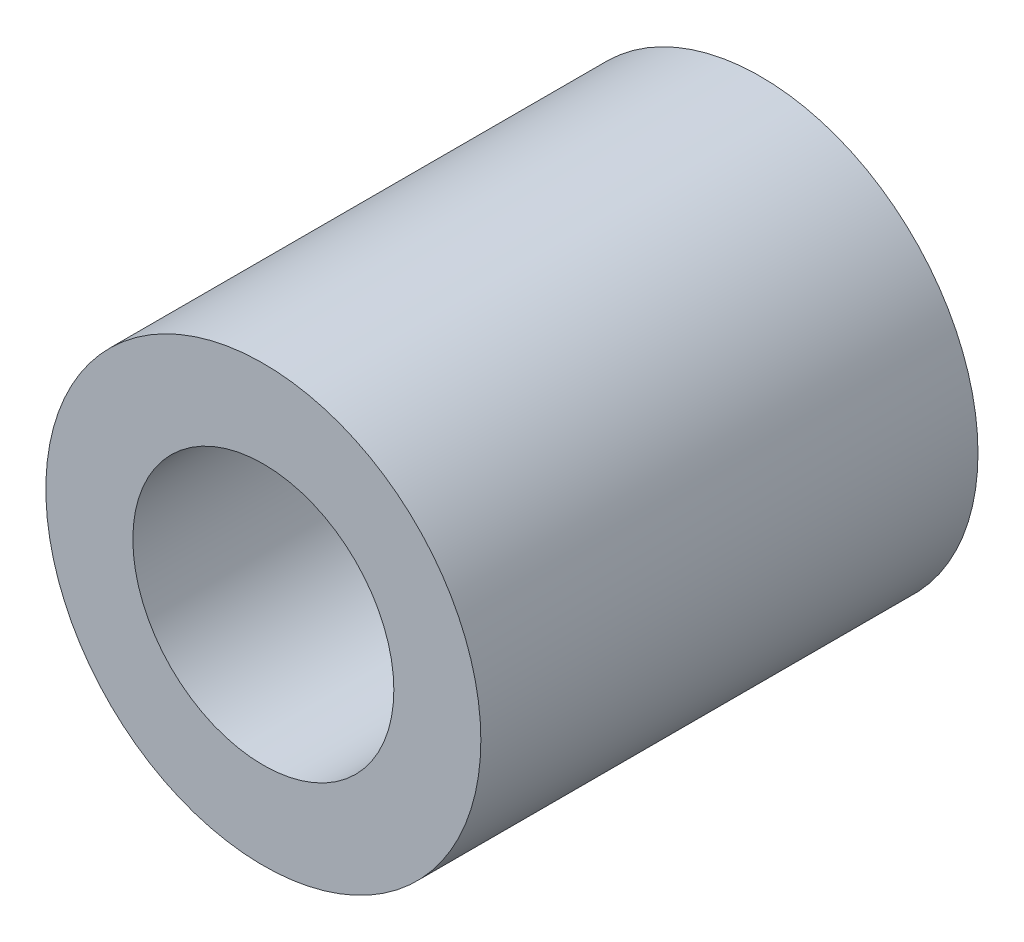
SolidWorks part; units mm, degrees
ref_plane "前视基准面" through (0, 0, 0) normal (0, 0, 1) x (1, 0, 0)
ref_plane "上视基准面" through (0, 0, 0) normal (0, 1, 0) x (1, 0, 0)
ref_plane "右视基准面" through (0, 0, 0) normal (1, 0, 0) x (0, 0, -1)
sketch "草图1" plane through (0, 0, 0) normal (0, 0, 1) x (1, 0, 0)
  circle A0 centre (0, 0) radius 2.1
  circle A1 centre (0, 0) radius 3.5
  dimension "D1" = 4.2
  dimension "D2" = 7
extrude "凸台-拉伸1" add sketch "草图1" along normal blind 8
